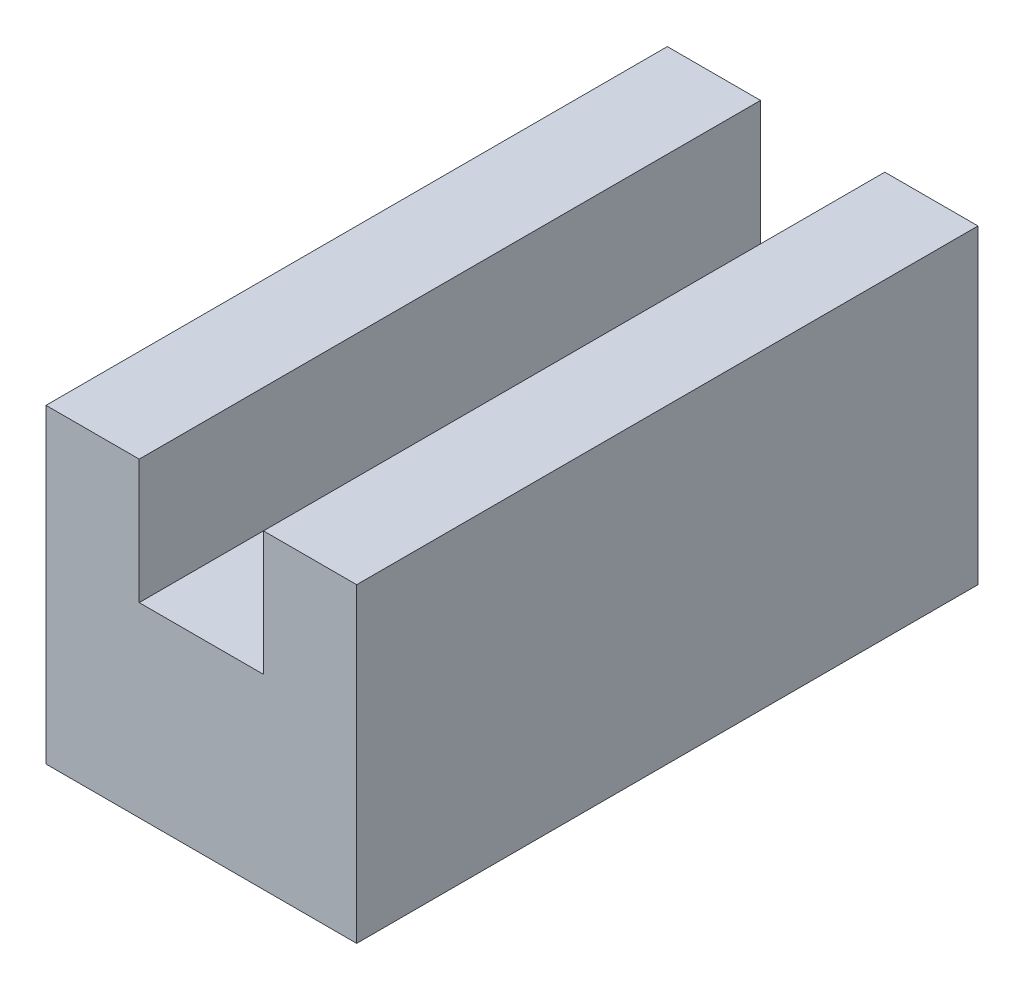
SolidWorks part; units mm, degrees
ref_plane "Front Plane" through (0, 0, 0) normal (0, 0, 1) x (1, 0, 0)
ref_plane "Top Plane" through (0, 0, 0) normal (0, 1, 0) x (1, 0, 0)
ref_plane "Right Plane" through (0, 0, 0) normal (1, 0, 0) x (0, 0, -1)
sketch "Sketch1" plane through (0, 0, 0) normal (0, 0, 1) x (1, 0, 0)
  line L1 (0, 0) -> (5, 0)
  line L2 (0, 0) -> (0, 5)
  line L3 (0, 5) -> (5, 5)
  line L4 (5, 0) -> (5, 5)
  dimension "D1" = 5
  dimension "D2" = 5
extrude "Boss-Extrude1" add sketch "Sketch1" along normal blind 10
sketch "Sketch2" plane through (0, 5, 0) normal (0, 1, 0) x (1, 0, 0)
  line L0 (5, 0) -> (0, 0) construction
  line L1 (1.5, 0) -> (3.5, 0)
  line L2 (1.5, 0) -> (1.5, -10)
  line L3 (1.5, -10) -> (3.5, -10)
  line L4 (3.5, 0) -> (3.5, -10)
  line L5 (5, -10) -> (0, -10) construction
  line L6 (0, -10) -> (0, 0) construction
  dimension "D1" = 2
  dimension "D2" = 1.5
extrude "Cut-Extrude1" cut sketch "Sketch2" against normal blind 2
